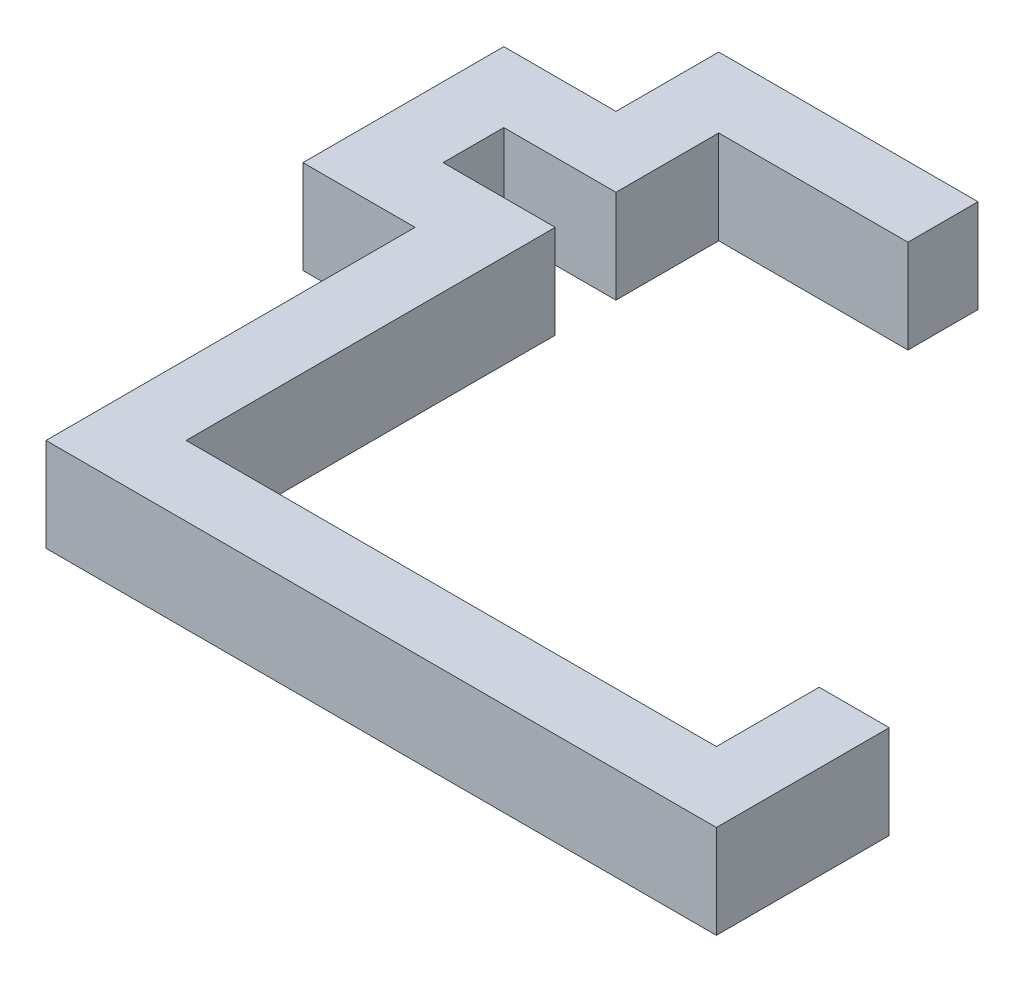
SolidWorks part; units mm, degrees
ref_plane "Front Plane" through (0, 0, 0) normal (0, 0, 1) x (1, 0, 0)
ref_plane "Top Plane" through (0, 0, 0) normal (0, 1, 0) x (1, 0, 0)
ref_plane "Right Plane" through (0, 0, 0) normal (1, 0, 0) x (0, 0, -1)
sketch "Sketch1" plane through (0, 0, 0) normal (0, 1, 0) x (1, 0, 0)
  line L0 (0, 0) -> (-22.7, 0)
  line L1 (-22.7, 0) -> (-22.7, 15.8)
  line L2 (-22.7, 15.8) -> (-27.5, 15.8)
  line L3 (-27.5, 15.8) -> (-27.5, 18.4)
  line L4 (-27.5, 18.4) -> (-22.7, 18.4)
  line L5 (-22.7, 18.4) -> (-22.7, 22.8)
  line L6 (-22.7, 22.8) -> (-14.6, 22.8)
  line L7 (-14.6, 22.8) -> (-14.6, 25.8)
  line L8 (-14.6, 25.8) -> (-25.7, 25.8)
  line L9 (-25.7, 25.8) -> (-25.7, 21.4)
  line L10 (-25.7, 21.4) -> (-30.5, 21.4)
  line L11 (-30.5, 21.4) -> (-30.5, 12.8)
  line L12 (-30.5, 12.8) -> (-25.7, 12.8)
  line L13 (-25.7, 12.8) -> (-25.7, -3)
  line L14 (-25.7, -3) -> (3, -3)
  line L15 (3, -3) -> (3, 4.4)
  line L16 (3, 4.4) -> (0, 4.4)
  line L17 (0, 4.4) -> (0, 0)
  line L18 (-20.3849, 22.8) -> (-20.3849, 25.8) construction
  line L19 (-30.5, 17.4855) -> (-27.5, 17.4855) construction
  line L20 (-26.3183, 18.4) -> (-26.3183, 21.4) construction
  line L21 (-26.6067, 12.8) -> (-26.6067, 15.8) construction
  line L22 (-25.7, 16.4649) -> (-22.7, 16.4649) construction
  line L23 (-18.3967, -3) -> (-18.3967, 0) construction
  line L25 (0, 4.1412) -> (3, 4.1412) construction
  dimension "D1" = 8.1
  dimension "D2" = 4.4
  dimension "D3" = 4.8
  dimension "D4" = 3
  dimension "D5" = 2.6
  dimension "D6" = 15.8
  dimension "D7" = 22.7
  dimension "D8" = 4.4
extrude "Boss-Extrude1" add sketch "Sketch1" along normal blind 4
